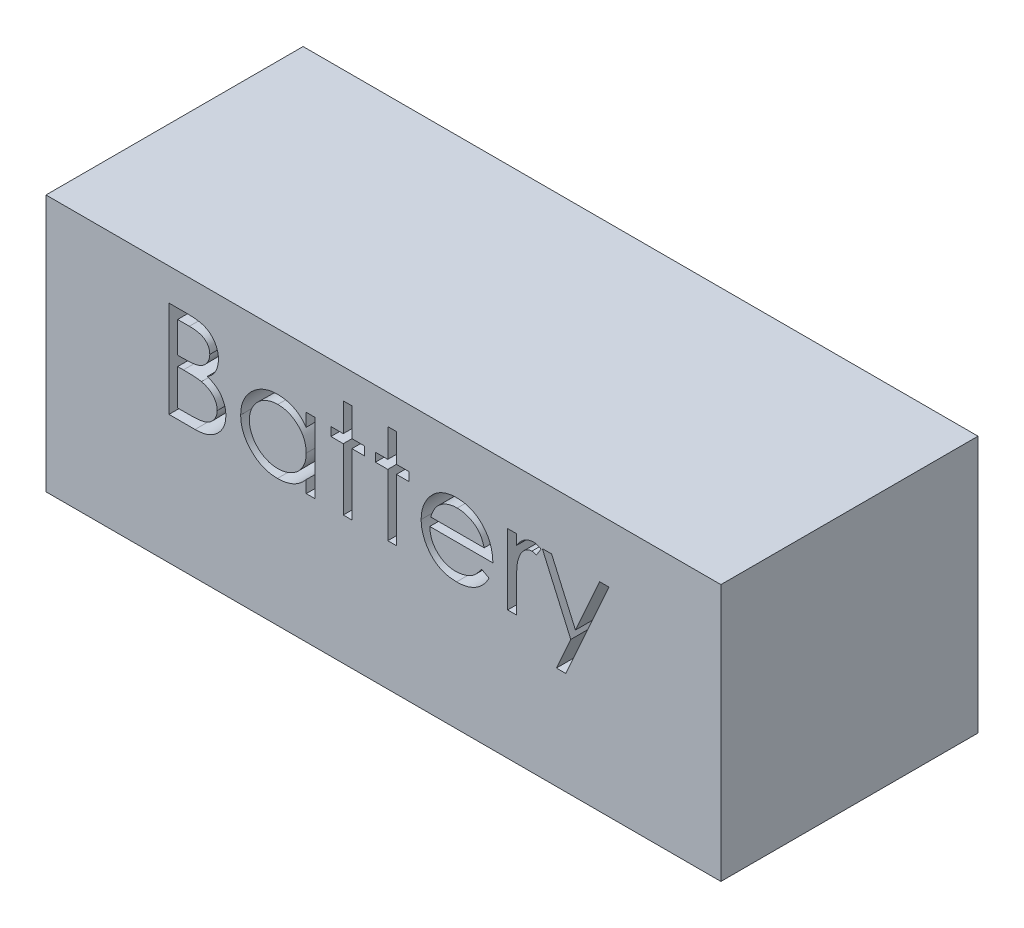
SolidWorks part; units mm, degrees
ref_plane "Front Plane" through (0, 0, 0) normal (0, 0, 1) x (1, 0, 0)
ref_plane "Top Plane" through (0, 0, 0) normal (0, 1, 0) x (1, 0, 0)
ref_plane "Right Plane" through (0, 0, 0) normal (1, 0, 0) x (0, 0, -1)
sketch "Sketch1" plane through (0, 0, 0) normal (0, 0, 1) x (1, 0, 0)
  line L1 (-78.6034, 48.6024) -> (54.7466, 48.6024)
  line L2 (-78.6034, 48.6024) -> (-78.6034, -2.1976)
  line L3 (-78.6034, -2.1976) -> (54.7466, -2.1976)
  line L4 (54.7466, 48.6024) -> (54.7466, -2.1976)
  dimension "D1" = 133.35
  dimension "D2" = 50.8
extrude "Boss-Extrude1" add sketch "Sketch1" along normal blind 50.8
sketch "Sketch2" plane through (0, 0, 50.8) normal (0, 0, 1) x (1, 0, 0)
  line L0 (-78.6034, 23.2024) -> (54.7466, 23.2024) construction
  line L1 (-78.6034, 48.6024) -> (-78.6034, -2.1976) construction
  line L2 (54.7466, -2.1976) -> (54.7466, 48.6024) construction
  text T0 "Battery" font "Century Gothic" height in points 72
extrude "Cut-Extrude2" cut sketch "Sketch2" against normal through all
